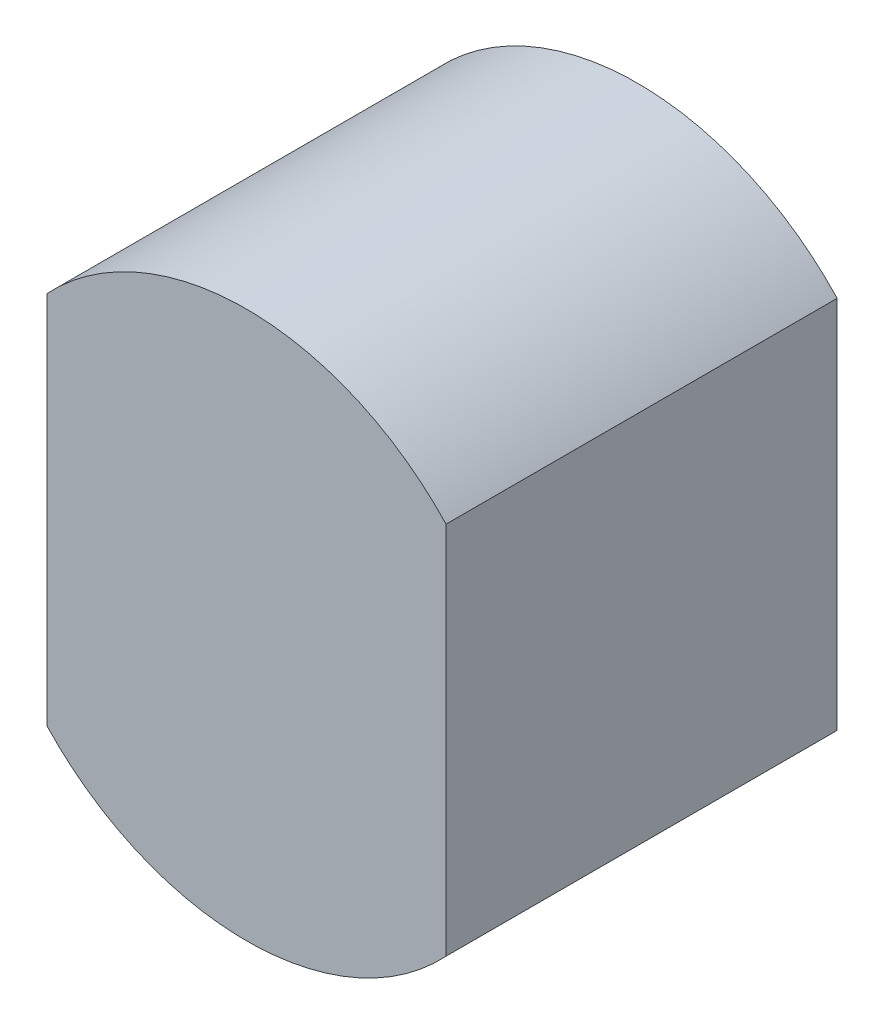
SolidWorks part; units mm, degrees
ref_plane "Front Plane" through (0, 0, 0) normal (0, 0, 1) x (1, 0, 0)
ref_plane "Top Plane" through (0, 0, 0) normal (0, 1, 0) x (1, 0, 0)
ref_plane "Right Plane" through (0, 0, 0) normal (1, 0, 0) x (0, 0, -1)
sketch "Sketch1" plane through (0, 0, 0) normal (0, 0, 1) x (1, 0, 0)
  line L2 (25.019, 23.449) -> (25.019, -23.449)
  line L4 (-25.019, 23.449) -> (-25.019, -23.449)
  line L5 (25.019, 23.449) -> (-25.019, -23.449) construction
  line L6 (25.019, -23.449) -> (-25.019, 23.449) construction
  arc A0 (-25.019, -23.449) -> (25.019, -23.449) centre (0, 0) ccw
  arc A1 (25.019, 23.449) -> (-25.019, 23.449) centre (0, 0) ccw
  point P7 (25.019, -35.8671)
  dimension "D2" = 68.58
  dimension "D1" = 50.038
extrude "Boss-Extrude1" add sketch "Sketch1" along normal blind 49.022
